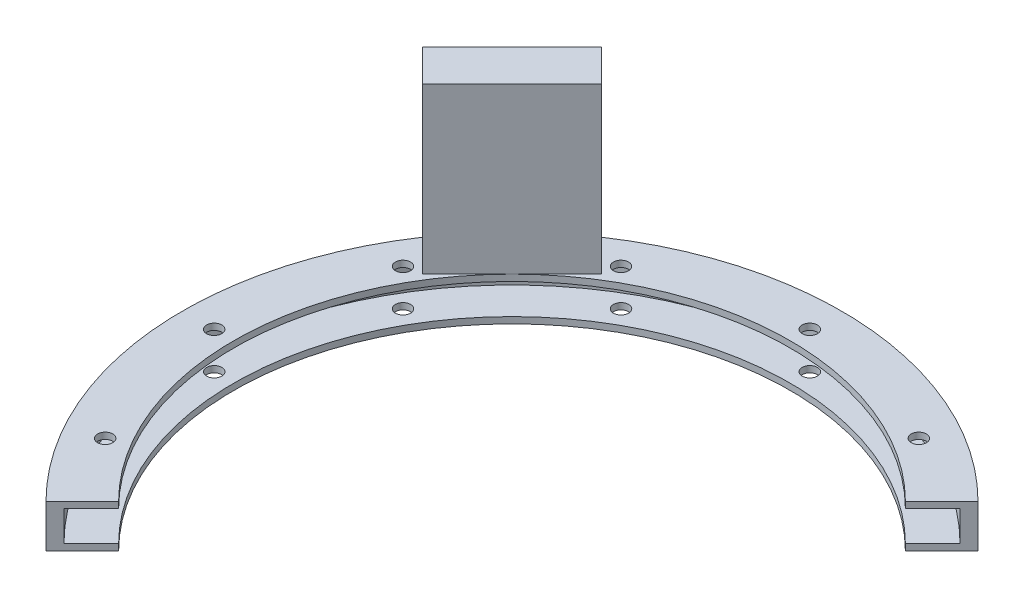
SolidWorks part; units mm, degrees
ref_plane "Front Plane" through (0, 0, 0) normal (0, 0, 1) x (1, 0, 0)
ref_plane "Top Plane" through (0, 0, 0) normal (0, 1, 0) x (1, 0, 0)
ref_plane "Right Plane" through (0, 0, 0) normal (1, 0, 0) x (0, 0, -1)
sketch "Sketch1" plane through (0, 0, 0) normal (0, 1, 0) x (1, 0, 0)
  line L0 (0, 0) -> (0, 260) construction
  circle A0 centre (0, 0) radius 250 construction
  circle A1 centre (0, 0) radius 219.5
  circle A2 centre (0, 0) radius 260
  circle A3 centre (0, 0) radius 235 construction
  circle A4 centre (0, 235) radius 6
  circle A5 centre (117.5, 203.516) radius 6
  circle A6 centre (203.516, 117.5) radius 6
  circle A7 centre (235, 0) radius 6
  circle A8 centre (203.516, -117.5) radius 6
  circle A9 centre (117.5, -203.516) radius 6
  circle A10 centre (0, -235) radius 6
  circle A11 centre (-117.5, -203.516) radius 6
  circle A12 centre (-203.516, -117.5) radius 6
  circle A13 centre (-235, 0) radius 6
  circle A14 centre (-203.516, 117.5) radius 6
  circle A15 centre (-117.5, 203.516) radius 6
  point P34 (0, 0)
  dimension "D1" = 500
  dimension "D2" = 439
  dimension "D3" = 520
  dimension "D4" = 470
  dimension "D5" = 12
  dimension "D6" = 12
extrude "Boss-Extrude1" add sketch "Sketch1" along normal mid plane 34 contours A2 A15 A14 A13 A12 A11 A10 A9 A8 A7 A6 A5 A4 A1
sketch "Sketch2" plane through (0, 0, 0) normal (0, 1, 0) x (1, 0, 0)
  circle A0 centre (0, 0) radius 250
  dimension "D1" = 500
extrude "Cut-Extrude1" cut sketch "Sketch2" against normal mid plane 24
sketch "Sketch3" plane through (0, 17, 0) normal (0, 1, 0) x (1, 0, 0)
  line L0 (-183.8478, -183.8478) -> (183.8478, 183.8478)
  line L1 (-183.8478, -183.8478) -> (3.0089, -370.7044)
  line L2 (183.8478, 183.8478) -> (370.7044, -3.0089)
  line L3 (3.0089, -370.7044) -> (370.7044, -3.0089)
  line L4 (0, 0) -> (-260, 0) construction
  circle A0 centre (0, 0) radius 260 construction
  dimension "34" = 45
extrude "Cut-Extrude2" cut sketch "Sketch3" against normal through all
sketch "Sketch4" plane through (0, 17, 0) normal (0, 1, 0) x (1, 0, 0)
  line L0 (-215.7715, 145.0608) -> (-190.5653, 119.8546)
  line L1 (-215.7715, 145.0608) -> (-145.0608, 215.7715)
  line L2 (-190.5653, 119.8546) -> (-119.8546, 190.5653)
  line L3 (-145.0608, 215.7715) -> (-119.8546, 190.5653)
  line L4 (0, 0) -> (-196.9409, 196.9409) construction
  line L5 (0, 0) -> (-306.2448, 0) construction
  arc A0 (155.2099, 155.2099) -> (-155.2099, -155.2099) centre (0, 0) ccw construction
  arc A1 (183.8478, 183.8478) -> (-183.8478, -183.8478) centre (0, 0) ccw construction
  point P11 (-155.2099, 155.2099)
  point P12 (0, 0)
  dimension "D1" = 45
  dimension "D2" = 100
extrude "Boss-Extrude2" add sketch "Sketch4" along normal blind 130
